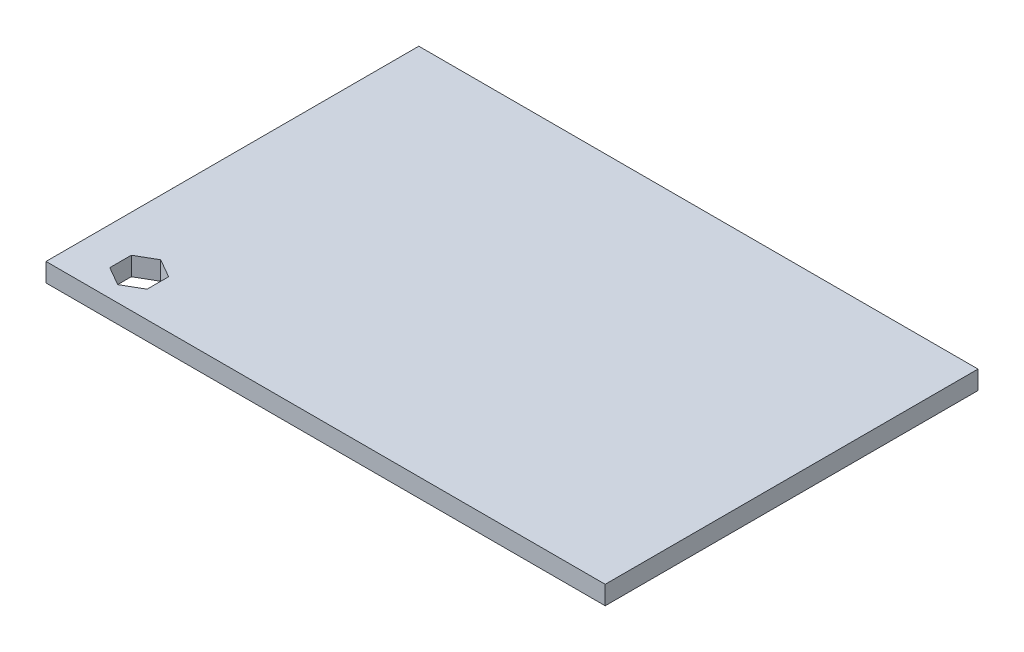
SolidWorks part; units mm, degrees
ref_plane "Front Plane" through (0, 0, 0) normal (0, 0, 1) x (1, 0, 0)
ref_plane "Top Plane" through (0, 0, 0) normal (0, 1, 0) x (1, 0, 0)
ref_plane "Right Plane" through (0, 0, 0) normal (1, 0, 0) x (0, 0, -1)
sketch "Sketch1" plane through (0, 0, 0) normal (0, 1, 0) x (1, 0, 0)
  line L1 (0, 0) -> (381, 0)
  line L2 (0, 0) -> (0, 254)
  line L3 (0, 254) -> (381, 254)
  line L4 (381, 0) -> (381, 254)
  dimension "D1" = 254
  dimension "D2" = 381
extrude "Boss-Extrude1" add sketch "Sketch1" along normal blind 12.7
sketch "Sketch2" plane through (0, 12.7, 0) normal (0, 1, 0) x (1, 0, 0)
  line L0 (38.1, 10.7353) -> (50.8, 18.0677)
  line L1 (38.1, 40.0647) -> (25.4, 32.7323)
  line L2 (25.4, 32.7323) -> (25.4, 18.0677)
  line L3 (25.4, 18.0677) -> (38.1, 10.7353)
  line L4 (50.8, 18.0677) -> (50.8, 32.7323)
  line L5 (50.8, 32.7323) -> (38.1, 40.0647)
  line L6 (0, 254) -> (0, 0) construction
  line L7 (0, 0) -> (381, 0) construction
  circle A0 centre (38.1, 25.4) radius 12.7 construction
  dimension "D1" = 25.4
  dimension "D2" = 25.4
  dimension "D3" = 25.4
extrude "Cut-Extrude1" cut sketch "Sketch2" against normal through all
